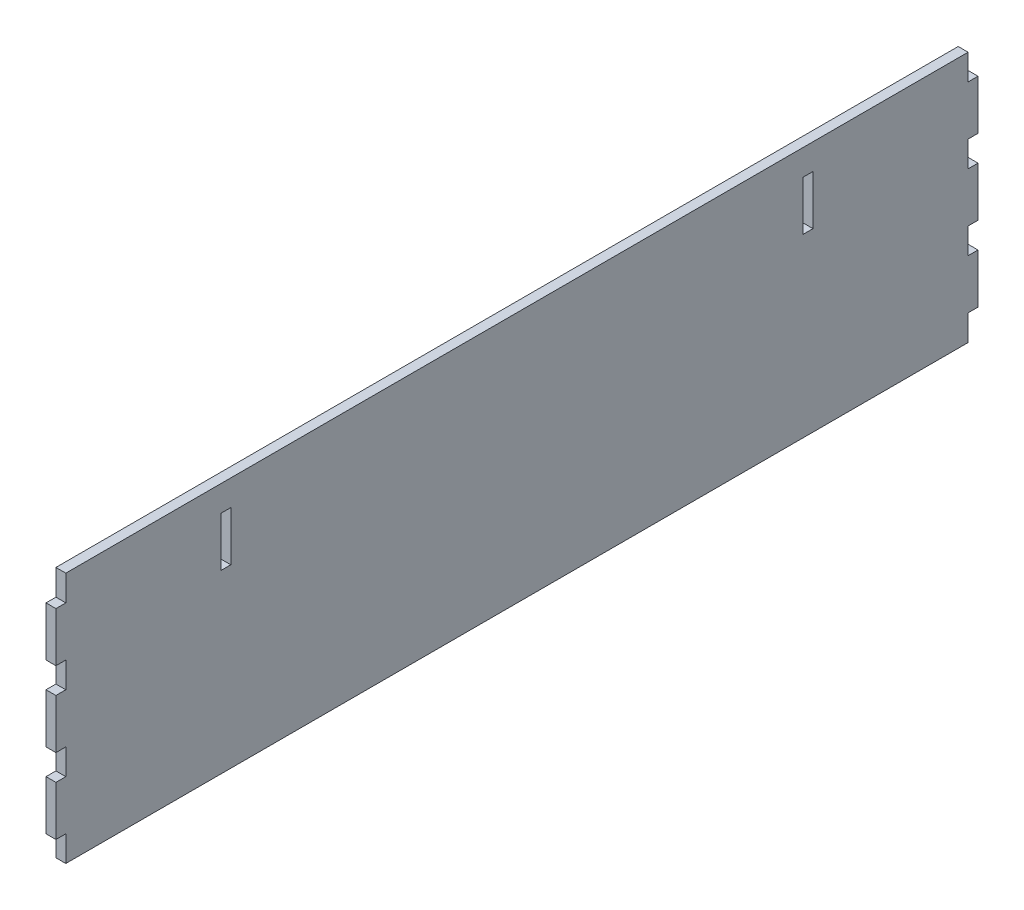
SolidWorks part; units mm, degrees
material "ENPH 253 Hardboard"
ref_plane "Front Plane" through (0, 0, 0) normal (0, 0, 1) x (1, 0, 0)
ref_plane "Top Plane" through (0, 0, 0) normal (0, 1, 0) x (1, 0, 0)
ref_plane "Right Plane" through (0, 0, 0) normal (1, 0, 0) x (0, 0, -1)
sketch "Sketch1" plane through (0, 0, 0) normal (1, 0, 0) x (0, 0, -1)
  line L1 (-139.7, 38.1) -> (139.7, 38.1)
  line L2 (-139.7, 38.1) -> (-139.7, -38.1)
  line L3 (-139.7, -38.1) -> (139.7, -38.1)
  line L4 (139.7, 38.1) -> (139.7, -38.1)
  line L5 (-139.7, 38.1) -> (139.7, -38.1) construction
  line L6 (-139.7, -38.1) -> (139.7, 38.1) construction
  point P0 (0, 0)
  dimension "D1" = 279.4
  dimension "D2" = 76.2
extrude "Boss-Extrude1" add sketch "Sketch1" against normal blind 3 contours L2 L3 L4 L1
sketch "Sketch3" plane through (-3, 0, 0) normal (-1, 0, 0) x (0, 0, 1)
  line L9 (-139.7, 38.1) -> (-136.7, 38.1)
  line L10 (-139.7, 38.1) -> (-139.7, 30.3)
  line L11 (-139.7, 30.3) -> (-136.7, 30.3)
  line L12 (-136.7, 38.1) -> (-136.7, 30.3)
  dimension "D9" = 7.8
  dimension "D10" = 3
extrude "Cut-Extrude1" cut sketch "Sketch3" against normal through all
pattern_linear "LPattern1" count 4 spacing 22.8 along (0, -1, 0) of "Cut-Extrude1"
mirror "Mirror1" about plane through (0, 0, 0) normal (0, 0, 1) of "LPattern1", "Cut-Extrude1"
sketch "Sketch5" plane through (-3, 0, 0) normal (-1, 0, 0) x (0, 0, 1)
  line L0 (-139.7, 30.3) -> (-139.7, 15.3) construction
  line L1 (-89.7, 30.3) -> (-86.7, 30.3)
  line L2 (-89.7, 30.3) -> (-89.7, 15.3)
  line L3 (-89.7, 15.3) -> (-86.7, 15.3)
  line L4 (-86.7, 30.3) -> (-86.7, 15.3)
  line L5 (136.7, 38.1) -> (-136.7, 38.1) construction
  dimension "D1" = 50
  dimension "D2" = 3
  dimension "D3" = 7.8
  dimension "D4" = 15
extrude "Cut-Extrude3" cut sketch "Sketch5" against normal blind 10
mirror "Mirror2" about plane through (0, 0, 0) normal (0, 0, 1) of "Cut-Extrude3"
